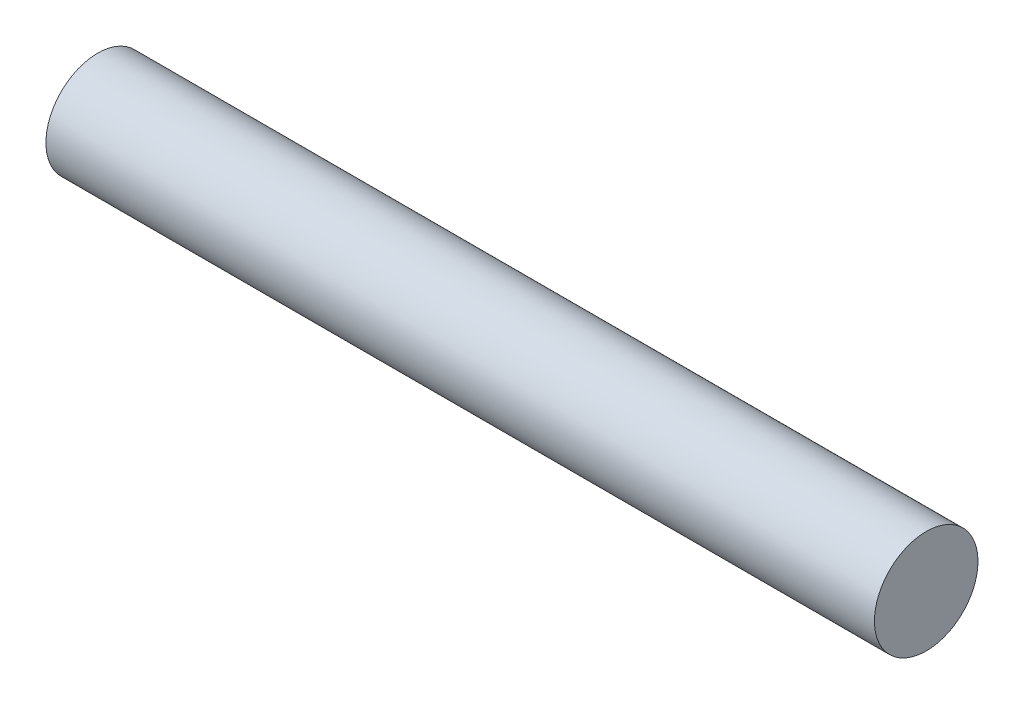
SolidWorks part; units mm, degrees
ref_plane "Front Plane" through (0, 0, 0) normal (0, 0, 1) x (1, 0, 0)
ref_plane "Top Plane" through (0, 0, 0) normal (0, 1, 0) x (1, 0, 0)
ref_plane "Right Plane" through (0, 0, 0) normal (1, 0, 0) x (0, 0, -1)
sketch "Sketch1" plane through (0, 0, 0) normal (1, 0, 0) x (0, 0, -1)
  circle A0 centre (0, 0) radius 2.5
  dimension "D1" = 5
extrude "Boss-Extrude1" add sketch "Sketch1" along normal blind 40
